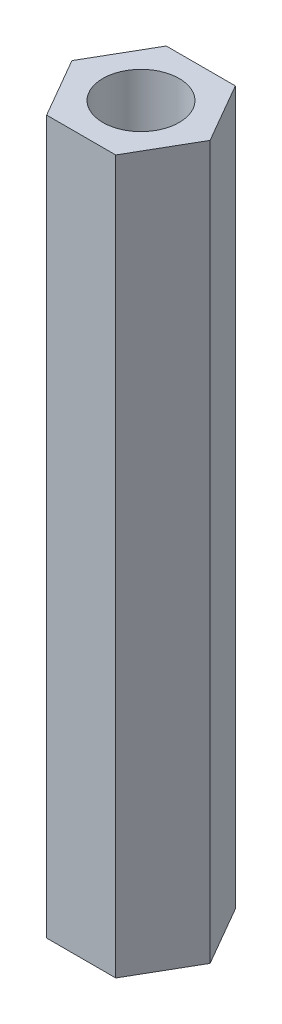
SolidWorks part; units mm, degrees
ref_plane "Front Plane" through (0, 0, 0) normal (0, 0, 1) x (1, 0, 0)
ref_plane "Top Plane" through (0, 0, 0) normal (0, 1, 0) x (1, 0, 0)
ref_plane "Right Plane" through (0, 0, 0) normal (1, 0, 0) x (0, 0, -1)
sketch "Sketch1" plane through (0, 0, 0) normal (0, 1, 0) x (1, 0, 0)
  line L1 (-2.7135, 0) -> (-1.3568, -2.35)
  line L2 (-1.3568, -2.35) -> (1.3568, -2.35)
  line L3 (1.3568, -2.35) -> (2.7135, 0)
  line L4 (2.7135, 0) -> (1.3568, 2.35)
  line L5 (1.3568, 2.35) -> (-1.3568, 2.35)
  line L6 (-1.3568, 2.35) -> (-2.7135, 0)
  circle A0 centre (0, 0) radius 1.5
  circle A1 centre (0, 0) radius 2.35 construction
  dimension "D1" = 3
  dimension "D2" = 4.7
extrude "Boss-Extrude1" add sketch "Sketch1" along normal blind 28
